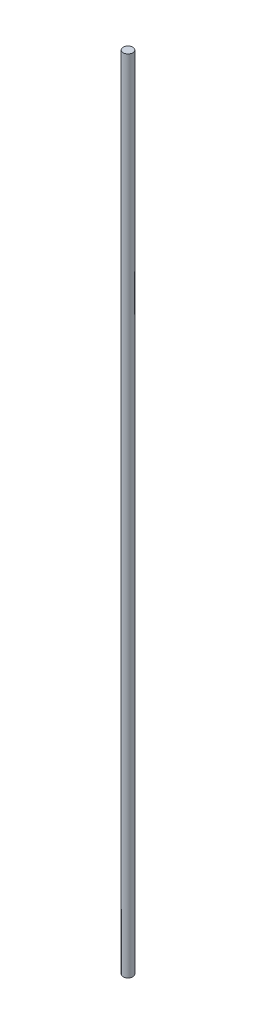
SolidWorks part; units mm, degrees
ref_plane "Front Plane" through (0, 0, 0) normal (0, 0, 1) x (1, 0, 0)
ref_plane "Top Plane" through (0, 0, 0) normal (0, 1, 0) x (1, 0, 0)
ref_plane "Right Plane" through (0, 0, 0) normal (1, 0, 0) x (0, 0, -1)
sketch "Sketch1" plane through (0, 0, 0) normal (1, 0, 0) x (0, 0, -1)
  line L0 (0, 492.4948) -> (0, -2.5052) construction
  line L1 (3, 492.4948) -> (3, -2.5052)
  line L2 (3, -2.5052) -> (0, -2.5052)
  line L3 (0, 492.4948) -> (3, 492.4948)
  line L4 (0, 492.4948) -> (0, -2.5052)
  dimension "D1" = 3
  dimension "D2" = 495
  dimension "3" = 3
revolve "Revolve1" add sketch "Sketch1" angle 360 about L1
